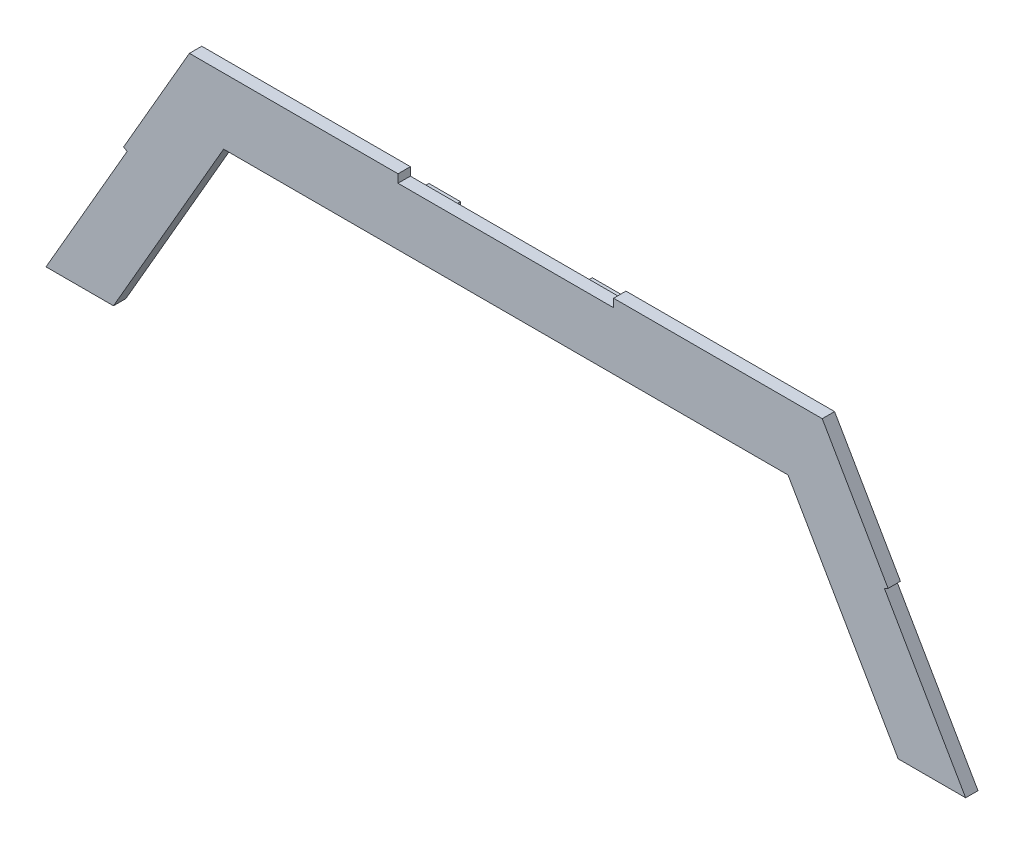
SolidWorks part; units mm, degrees
material "Balsa"
ref_plane "Front Plane" through (0, 0, 0) normal (0, 0, 1) x (1, 0, 0)
ref_plane "Top Plane" through (0, 0, 0) normal (0, 1, 0) x (1, 0, 0)
ref_plane "Right Plane" through (0, 0, 0) normal (1, 0, 0) x (0, 0, -1)
sketch "Sketch1" plane through (0, 0, 0) normal (0, 0, 1) x (1, 0, 0)
  line L0 (-122.047, 202.56) -> (-179.197, 103.5733)
  line L1 (-179.197, 103.5733) -> (-151.3341, 103.5733)
  line L2 (-151.3341, 103.5733) -> (-108.8488, 177.16)
  line L3 (-108.8488, 177.16) -> (108.8488, 177.16)
  line L4 (0, 0) -> (0, 354.32) construction
  line L5 (-122.047, 202.56) -> (-41.5739, 202.56)
  line L6 (-41.5739, 202.56) -> (-41.5915, 199.3851)
  line L7 (-41.5915, 199.3851) -> (41.5915, 199.3851)
  line L8 (41.5739, 202.56) -> (41.5915, 199.3851)
  line L9 (122.047, 202.56) -> (41.5739, 202.56)
  line L10 (122.047, 202.56) -> (179.197, 103.5733)
  line L11 (179.197, 103.5733) -> (151.3341, 103.5733)
  line L12 (151.3341, 103.5733) -> (108.8488, 177.16)
  point P18 (0, 177.16)
  dimension "D1" = 3.175
  dimension "D2" = 244.094
  dimension "D3" = 83.183
  dimension "D4" = 24.13
  dimension "D5" = 25.4
  dimension "D6" = 114.3
extrude "Boss-Extrude1" add sketch "Sketch1" along normal blind 4.7625
sketch "Sketch2" plane through (0, 0, 4.7625) normal (0, 0, 1) x (1, 0, 0)
  line L1 (179.197, 103.5733) -> (122.047, 202.56) construction
  line L7 (183.007, 96.9742) -> (181.6322, 96.1805)
  line L11 (146.0722, 157.7722) -> (181.6322, 96.1805)
  line L12 (183.007, 96.9742) -> (147.447, 158.5659)
  line L13 (146.0722, 157.7722) -> (147.447, 158.5659)
  line L14 (0, 0) -> (0, 246.0761) construction
  line L15 (-183.007, 96.9742) -> (-181.6322, 96.1805)
  line L16 (-146.0722, 157.7722) -> (-147.447, 158.5659)
  line L17 (-146.0722, 157.7722) -> (-181.6322, 96.1805)
  line L18 (-183.007, 96.9742) -> (-147.447, 158.5659)
  dimension "D1" = 71.12
  dimension "D2" = 1.5875
  dimension "D3" = 1.5875
  dimension "D4" = 50.8
extrude "Cut-Extrude2" cut sketch "Sketch2" against normal through all
sketch "Sketch3" plane through (0, 0, 0) normal (0, 0, -1) x (-1, 0, 0)
  line L0 (-37.592, 197.3531) -> (-37.592, 182.1131)
  line L1 (-37.592, 182.1131) -> (-25.4, 182.1131)
  line L2 (-25.4, 182.1131) -> (-25.4, 197.3531)
  line L3 (-25.4, 197.3531) -> (-37.592, 197.3531)
  line L4 (-41.5915, 199.3851) -> (41.5915, 199.3851) construction
  line L5 (0, 0) -> (0, 226.8084) construction
  line L6 (25.4, 182.1131) -> (25.4, 197.3531)
  line L7 (37.592, 182.1131) -> (25.4, 182.1131)
  line L8 (37.592, 197.3531) -> (37.592, 182.1131)
  line L9 (25.4, 197.3531) -> (37.592, 197.3531)
  dimension "D1" = 12.192
  dimension "D2" = 17.272
  dimension "D3" = 25.4
  dimension "D4" = 15.24
extrude "Boss-Extrude2" add sketch "Sketch3" along normal blind 3.175
